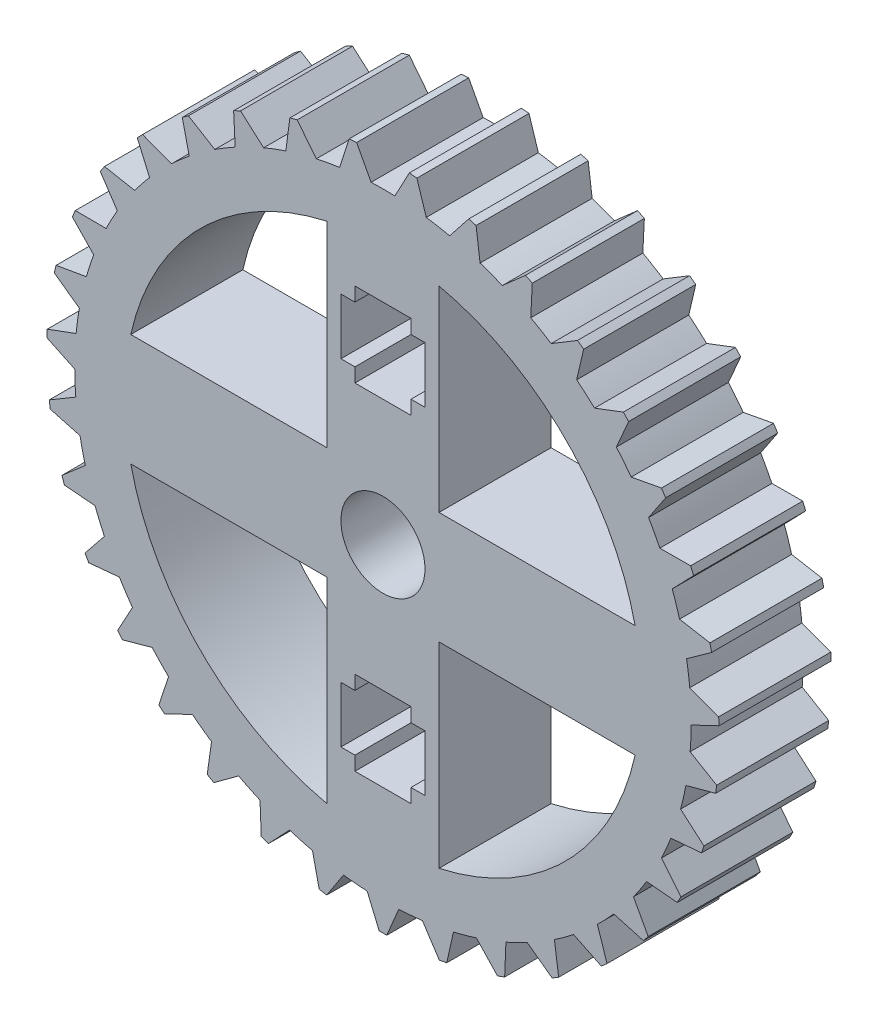
SolidWorks part; units mm, degrees
ref_plane "Front Plane" through (0, 0, 0) normal (0, 0, 1) x (1, 0, 0)
ref_plane "Top Plane" through (0, 0, 0) normal (0, 1, 0) x (1, 0, 0)
ref_plane "Right Plane" through (0, 0, 0) normal (1, 0, 0) x (0, 0, -1)
sketch "Sketch1" plane through (0, 0, 0) normal (0, 0, 1) x (1, 0, 0)
  circle A0 centre (0, 0) radius 6
  dimension "D1" = 12
extrude "Boss-Extrude1" add sketch "Sketch1" along normal blind 2
sketch "Sketch2" plane through (0, 0, 2) normal (0, 0, 1) x (1, 0, 0)
  line L0 (-9.4567, 0) -> (14.3424, 0) construction
  line L1 (0, 7.7767) -> (0, -9.0995) construction
  line L2 (-1, 1) -> (-4.5, 1)
  line L3 (-1, 1) -> (-1, 4.5)
  arc A0 (-1, 4.5) -> (-4.5, 1) centre (0, 0) ccw
  dimension "D1" = 1
  dimension "D2" = 1
  dimension "D3" = 3.5
extrude "Cut-Extrude1" cut sketch "Sketch2" against normal blind 2
mirror "Mirror1" about plane through (0, 0, 0) normal (1, 0, 0) of "Cut-Extrude1"
mirror "Mirror2" about plane through (0, 0, 0) normal (0, 1, 0) of "Mirror1", "Cut-Extrude1"
sketch "Sketch3" plane through (0, 0, 2) normal (0, 0, 1) x (1, 0, 0)
  circle A0 centre (0, 0) radius 0.75
  dimension "D1" = 1.5
sketch "Sketch4" plane through (0, 0, 2) normal (0, 0, 1) x (1, 0, 0)
  line L1 (0.75, 2.25) -> (-0.75, 2.25)
  line L2 (0.75, 2.25) -> (0.75, 3.75)
  line L3 (0.75, 3.75) -> (-0.75, 3.75)
  line L4 (-0.75, 2.25) -> (-0.75, 3.75)
  line L5 (0.75, 2.25) -> (-0.75, 3.75) construction
  line L6 (0.75, 3.75) -> (-0.75, 2.25) construction
  line L7 (-0.75, 3.75) -> (-0.5, 3.75)
  line L8 (-0.75, 3.75) -> (-0.75, 3.5)
  line L9 (-0.75, 3.5) -> (-0.5, 3.5)
  line L10 (-0.5, 3.75) -> (-0.5, 3.5)
  line L11 (0.75, 3.75) -> (0.5, 3.75)
  line L12 (0.75, 3.75) -> (0.75, 3.5)
  line L13 (0.75, 3.5) -> (0.5, 3.5)
  line L14 (0.5, 3.75) -> (0.5, 3.5)
  line L15 (0.75, 2.25) -> (0.5, 2.25)
  line L16 (0.75, 2.25) -> (0.75, 2.5)
  line L17 (0.75, 2.5) -> (0.5, 2.5)
  line L18 (0.5, 2.25) -> (0.5, 2.5)
  line L19 (-0.75, 2.25) -> (-0.5, 2.25)
  line L20 (-0.75, 2.25) -> (-0.75, 2.5)
  line L21 (-0.75, 2.5) -> (-0.5, 2.5)
  line L22 (-0.5, 2.25) -> (-0.5, 2.5)
  point P0 (0, 3)
  dimension "D1" = 3
  dimension "D2" = 1.5
  dimension "D3" = 0.25
  dimension "D4" = 0.25
  dimension "D5" = 0.25
  dimension "D6" = 0.25
extrude "Cut-Extrude5" cut sketch "Sketch3" against normal blind 2
extrude "Cut-Extrude6" cut sketch "Sketch4" against normal blind 2 contours L22 L1 L18 L17 L2 L13 L14 L3 L10 L9 L4 L21
mirror "Mirror3" about plane through (0, 0, 0) normal (0, 1, 0) of "Cut-Extrude6"
sketch "Sketch6" plane through (0, 0, 2) normal (0, 0, 1) x (1, 0, 0)
  line L0 (0, 3.2019) -> (0, 7.5234) construction
  line L1 (-0.47, 5.9816) -> (-0.2118, 5.4959)
  line L2 (0.47, 5.9816) -> (0.2118, 5.4959)
  circle A0 centre (0, 0) radius 5.5
  circle A1 centre (0, 0) radius 6 construction
  circle M23 centre (0, 0) radius 6
  dimension "D1" = 11
  dimension "D2" = 28
  dimension "D3" = 0.47
extrude "Cut-Extrude8" cut sketch "Sketch6" against normal blind 2 contours A0 L0 L1 M23 | L0 A0 L2 M23
pattern_circular "CirPattern2" count 35 over 360 about axis through (0, 0, 0) along (0, 0, 1) of "Cut-Extrude8"
